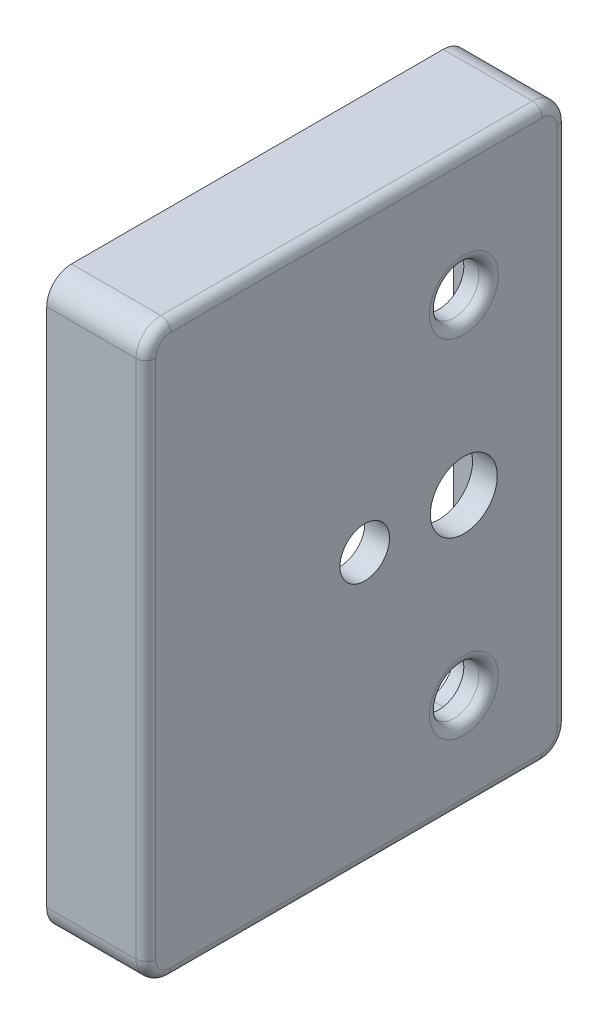
SolidWorks part; units mm, degrees
ref_plane "Front Plane" through (0, 0, 0) normal (0, 0, 1) x (1, 0, 0)
ref_plane "Top Plane" through (0, 0, 0) normal (0, 1, 0) x (1, 0, 0)
ref_plane "Right Plane" through (0, 0, 0) normal (1, 0, 0) x (0, 0, -1)
sketch "Sketch1" plane through (0, 0, 0) normal (1, 0, 0) x (0, 0, -1)
  line L1 (-14.6419, 58.42) -> (28.5381, 58.42)
  line L2 (-14.6419, 58.42) -> (-14.6419, 0)
  line L3 (-14.6419, 0) -> (28.5381, 0)
  line L4 (28.5381, 58.42) -> (28.5381, 0)
  dimension "D1" = 58.42
  dimension "D2" = 43.18
extrude "Boss-Extrude1" add sketch "Sketch1" along normal blind 10.16
sketch "Sketch2" plane through (0, 0, 0) normal (-1, 0, 0) x (0, 0, 1)
  line L0 (14.6419, 0) -> (-28.5381, 0) construction
  line L1 (-25.9981, 5.08) -> (12.1019, 5.08)
  line L2 (-25.9981, 5.08) -> (-25.9981, 50.8)
  line L3 (-25.9981, 50.8) -> (12.1019, 50.8)
  line L4 (12.1019, 5.08) -> (12.1019, 50.8)
  line L5 (-28.5381, 0) -> (-28.5381, 58.42) construction
  line L6 (14.6419, 58.42) -> (14.6419, 0) construction
  circle A0 centre (-17.9608, 10.16) radius 2.54
  circle A1 centre (-17.9608, 45.72) radius 2.54
  circle A2 centre (-17.9608, 27.94) radius 3.429
  circle A3 centre (-7.8008, 27.94) radius 2.54
  dimension "D6" = 5.08
  dimension "D7" = 5.08
  dimension "D8" = 6.858
  dimension "D9" = 5.08
  dimension "D1" = 10.16
  dimension "D2" = 17.78
  dimension "D3" = 17.78
  dimension "D4" = 27.94
  dimension "D5" = 45.72
  dimension "D10" = 5.08
  dimension "D11" = 2.54
  dimension "D12" = 2.54
  dimension "D13" = 19.9027
  dimension "D14" = 5.08
  dimension "D15" = 17.78
extrude "Cut-Extrude2" cut sketch "Sketch2" against normal through all contours A3 | A1 | A2 | A0
sketch "Sketch3" plane through (0, 0, 0) normal (-1, 0, 0) x (0, 0, 1)
  line L0 (-28.5381, 0) -> (-28.5381, 58.42) construction
  line L1 (-25.5381, 3.048) -> (11.5939, 3.048)
  line L2 (-25.5381, 3.048) -> (-25.5381, 55.372)
  line L3 (-25.5381, 55.372) -> (11.5939, 55.372)
  line L4 (11.5939, 3.048) -> (11.5939, 55.372)
  line L5 (14.6419, 58.42) -> (14.6419, 0) construction
  line L6 (-28.5381, 58.42) -> (14.6419, 58.42) construction
  line L7 (14.6419, 0) -> (-28.5381, 0) construction
  dimension "D1" = 3
  dimension "D2" = 3.048
  dimension "D3" = 3.048
  dimension "D4" = 3.048
extrude "Cut-Extrude3" cut sketch "Sketch3" against normal blind 7.62
sketch "Sketch4" plane through (0, 0, 0) normal (-1, 0, 0) x (0, 0, 1)
  line L0 (-25.5381, 3.048) -> (11.5939, 3.048) construction
  line L1 (-27.0621, 1.524) -> (13.1179, 1.524)
  line L2 (-27.0621, 1.524) -> (-27.0621, 56.896)
  line L3 (-27.0621, 56.896) -> (13.1179, 56.896)
  line L4 (13.1179, 1.524) -> (13.1179, 56.896)
  line L5 (11.5939, 55.372) -> (-25.5381, 55.372) construction
  line L6 (11.5939, 3.048) -> (11.5939, 55.372) construction
  line L7 (-25.5381, 55.372) -> (-25.5381, 3.048) construction
  point P4 (-1.9021, 43.5759)
  dimension "D1" = 1.524
  dimension "D2" = 1.524
  dimension "D3" = 1.524
  dimension "D4" = 1.524
extrude "Cut-Extrude4" cut sketch "Sketch4" against normal blind 3.81
fillet "Fillet1" radius 2.54 2 edges at (1.905, 1.524, -27.0621) (5.715, 3.048, -25.5381)
fillet "Fillet2" radius 2.54 2 edges at (5.715, 3.048, 11.5939) (1.905, 1.524, 13.1179)
fillet "Fillet3" radius 2.54 2 edges at (1.905, 56.896, 13.1179) (5.715, 55.372, 11.5939)
fillet "Fillet4" radius 2.54 2 edges at (1.905, 56.896, -27.0621) (5.715, 55.372, -25.5381)
fillet "Fillet5" radius 2.54 4 edges at (5.08, 0, -28.5381) (5.08, 0, 14.6419) (5.08, 58.42, -28.5381) (5.08, 58.42, 14.6419)
fillet "Fillet6" radius 1 8 edges at (10.16, 0.7439, 13.898) (10.16, 57.6761, 13.898) (10.16, 57.6761, -27.7941) (10.16, 0.7439, -27.7941) (10.16, 29.21, -28.5381) (10.16, 58.42, -6.9481) (10.16, 29.21, 14.6419) (10.16, 0, -6.9481)
fillet "Fillet7" radius 1 1 edges at (10.16, 45.72, -15.4208)
fillet "Fillet8" radius 1 1 edges at (10.16, 10.16, -15.4208)
